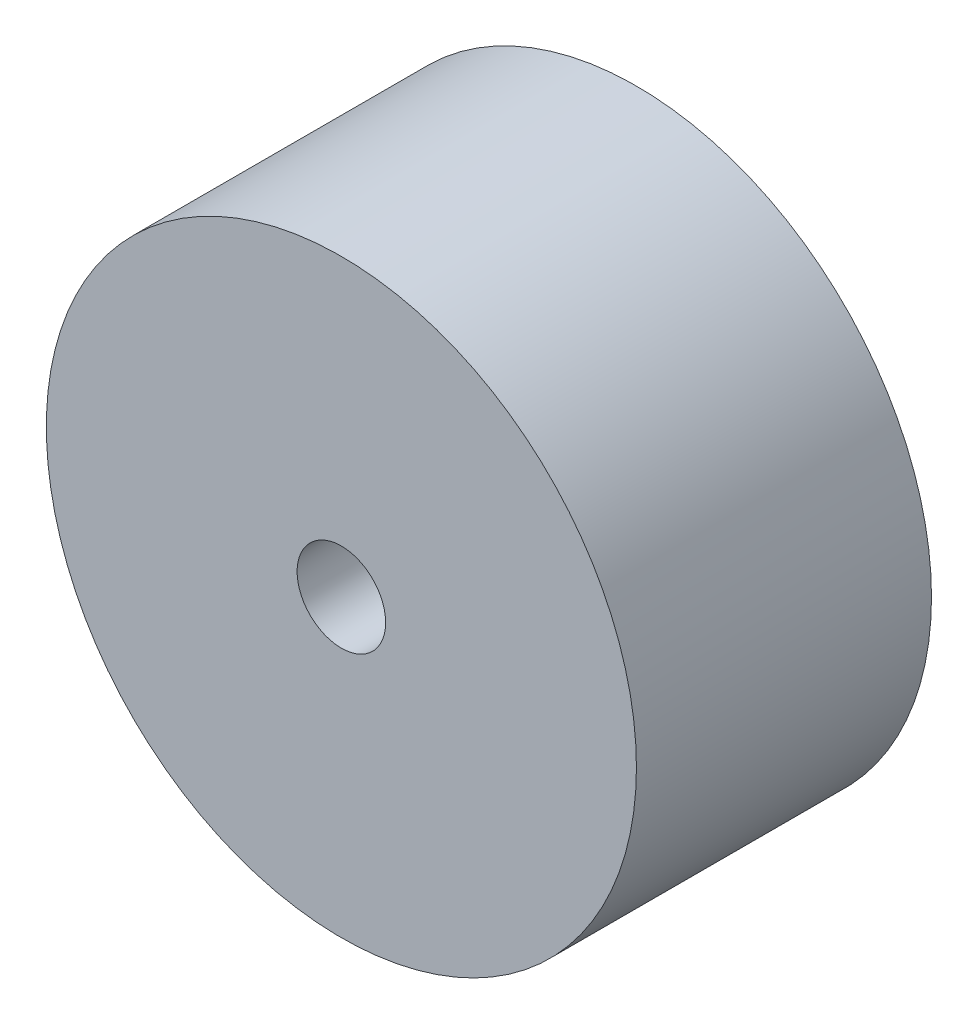
SolidWorks part; units mm, degrees
ref_plane "Front Plane" through (0, 0, 0) normal (0, 0, 1) x (1, 0, 0)
ref_plane "Top Plane" through (0, 0, 0) normal (0, 1, 0) x (1, 0, 0)
ref_plane "Right Plane" through (0, 0, 0) normal (1, 0, 0) x (0, 0, -1)
sketch "Sketch1" plane through (0, 0, 0) normal (0, 0, 1) x (1, 0, 0)
  circle A0 centre (0, 0) radius 50
  dimension "D1" = 100
extrude "Boss-Extrude1" add sketch "Sketch1" along normal blind 50
sketch "Sketch2" plane through (0, 0, 50) normal (0, 0, 1) x (1, 0, 0)
  circle A0 centre (0, 0) radius 7.5
  dimension "D1" = 15
extrude "Cut-Extrude1" cut sketch "Sketch2" against normal blind 50
